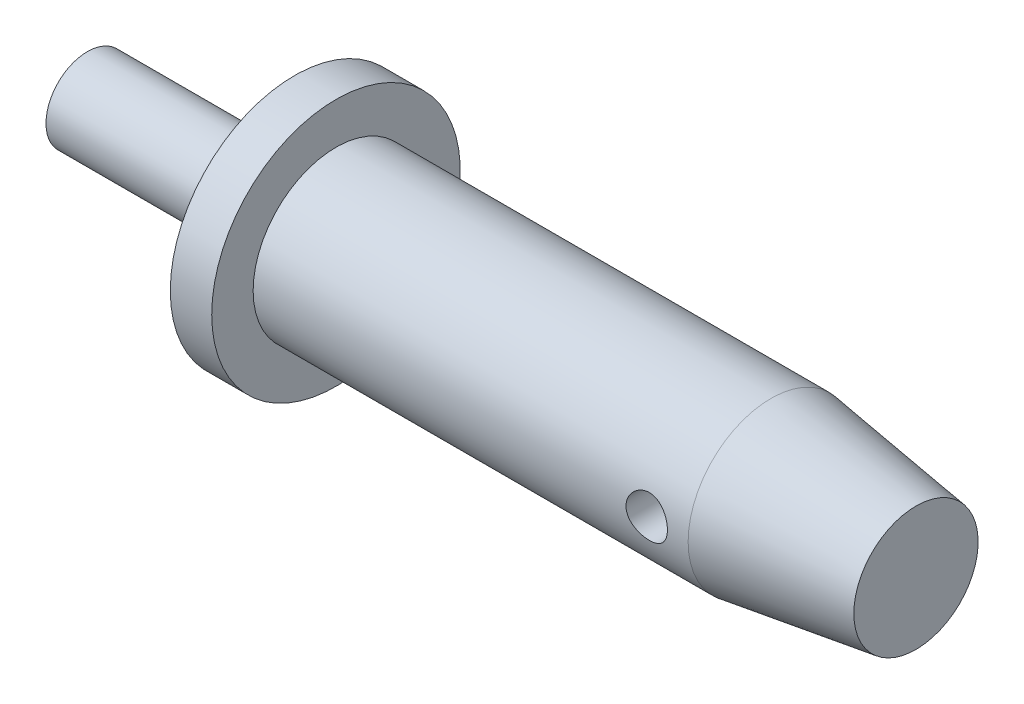
SolidWorks part; units mm, degrees
ref_plane "前视" through (0, 0, 0) normal (0, 0, 1) x (1, 0, 0)
ref_plane "上视" through (0, 0, 0) normal (0, 1, 0) x (1, 0, 0)
ref_plane "右视" through (0, 0, 0) normal (1, 0, 0) x (0, 0, -1)
sketch "草图1" plane through (0, 0, 0) normal (0, 0, 1) x (1, 0, 0)
  line L0 (0, 0) -> (200, 0)
  line L1 (0, 0) -> (0, 10)
  line L2 (0, 10) -> (50, 10)
  line L3 (50, 10) -> (50, 30)
  line L4 (50, 30) -> (60, 30)
  line L5 (60, 30) -> (60, 20)
  line L6 (60, 20) -> (165, 20)
  line L7 (165, 20) -> (200, 15)
  line L8 (200, 15) -> (200, 0)
  dimension "D1" = 200
  dimension "D2" = 10
  dimension "D3" = 20
  dimension "D4" = 10
  dimension "D5" = 105
  dimension "D6" = 50
  dimension "D7" = 20
  dimension "D8" = 15
revolve "旋转1" add sketch "草图1" angle 360 about L0
ref_plane "基准面1" through (0, 0, 20) normal (0, 0, 1) x (1, 0, 0)
sketch "草图2" plane through (0, 0, 20) normal (0, 0, 1) x (1, 0, 0)
  line L0 (-1000, 0) -> (49000, 0) construction
  line L1 (60, -30) -> (60, 30) construction
  circle A0 centre (155, 0) radius 5
  dimension "D1" = 10
  dimension "D2" = 95
extrude "切除-拉伸1" cut sketch "草图2" against normal through all
